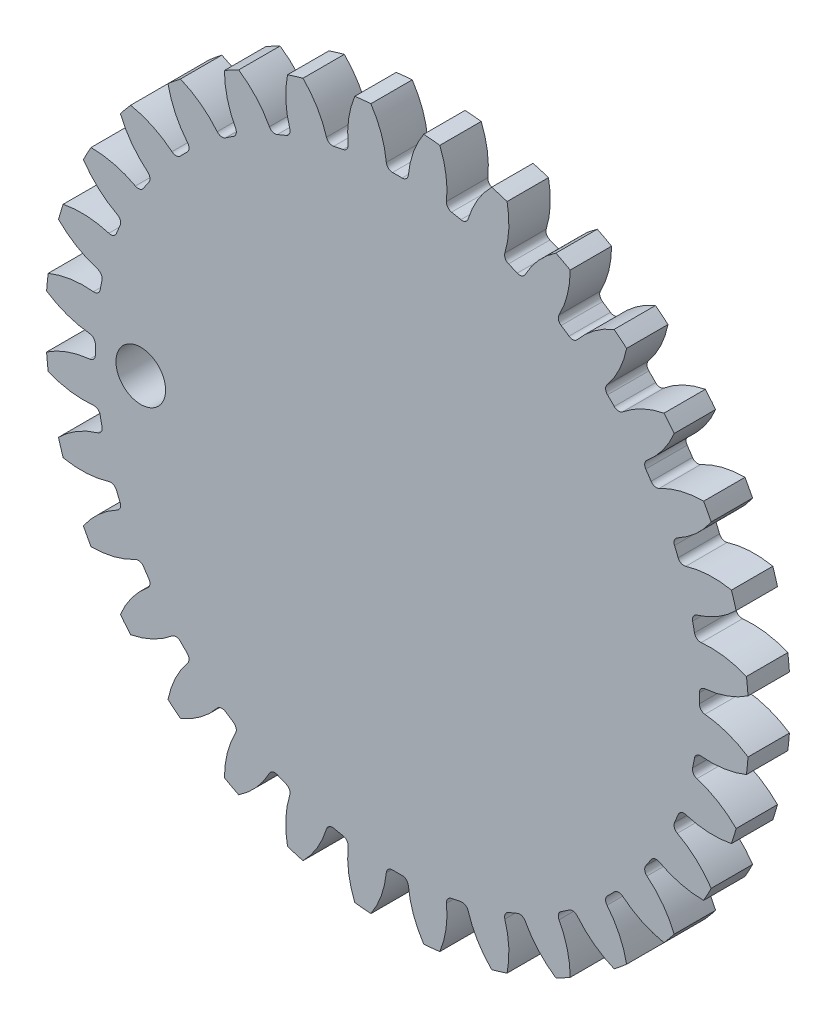
SolidWorks part; units mm, degrees
ref_plane "Front Plane" through (0, 0, 0) normal (0, 0, 1) x (1, 0, 0)
ref_plane "Top Plane" through (0, 0, 0) normal (0, 1, 0) x (1, 0, 0)
ref_plane "Right Plane" through (0, 0, 0) normal (1, 0, 0) x (0, 0, -1)
sketch "Sketch1" plane through (0, 0, 0) normal (0, 0, 1) x (1, 0, 0)
  circle A0 centre (0, 0) radius 50.8
  circle A1 centre (0, 0) radius 53.975
  circle A2 centre (0, 0) radius 46.355
  dimension "RootDiaCalc" = 101.6
  dimension "OutsideDiaCalc" = 107.95
  dimension "WholeDepthCalc" = 7.62
extrude "Boss-Extrude1" add sketch "Sketch1" along normal blind 6.35 contours A1
sketch "Sketch2" plane through (0, 0, 6.35) normal (0, 0, 1) x (1, 0, 0)
  line L0 (0, 0) -> (0, 53.975) construction
  line L1 (-2.4926, 50.7388) -> (2.4926, 50.7388) construction
  line L2 (-1.6341, 46.3262) -> (0, 0) construction
  line L3 (0, 43.8903) -> (-3.9819, 54.8306) construction
  line L4 (0, 0) -> (5.2905, 53.7151) construction
  line L5 (2.4926, 50.7388) -> (7.4539, 50.2502) construction
  circle A0 centre (0, 0) radius 53.975 construction
  arc A1 (-1.6341, 46.3262) -> (-4.749, 54.7695) centre (-16.0094, 45.8191) ccw
  arc A2 (1.6341, 46.3262) -> (4.749, 54.7695) centre (16.0094, 45.8191) cw
  circle A4 centre (0, 0) radius 46.355 construction
  arc A6 (1.6341, 46.3262) -> (-1.6341, 46.3262) centre (0, 0) ccw
  arc A7 (4.749, 54.7695) -> (-4.749, 54.7695) centre (0, 0) ccw
  circle A8 centre (0, 0) radius 53.975 construction
  circle A9 centre (0, 0) radius 50.8 construction
  dimension "SafetyOffset" = 1
  dimension "PressureAngleCalc" = 20
  dimension "AngleLineUpCalc" = 5.625
extrude "Cut-Extrude1" cut sketch "Sketch2" against normal up to surface (6.35 mm away) up to face at (53.975, 0, 0)
fillet "Fillet1" radius 0.9525 2 edges at (1.6341, 46.3262, 3.175) (-1.6341, 46.3262, 3.175)
pattern_circular "CirPattern1" count 32 over 360 about axis through (0, 0, 0) along (0, 0, 1) of "Cut-Extrude1", "Fillet1"
sketch "Sketch4" plane through (0, 0, 0) normal (0, 0, -1) x (-1, 0, 0)
  circle A0 centre (0, 0) radius 12.065
  dimension "D1" = 24.13
extrude "Boss-Extrude2" add sketch "Sketch4" along normal blind 6.35
sketch "Sketch7" plane through (0, 0, 0) normal (0, 0, -1) x (-1, 0, 0)
  line L1 (39.37, 0) -> (0, 0) construction
  circle A0 centre (39.37, 0) radius 3.81
  dimension "D1" = 7.62
  dimension "D2" = 39.37
extrude "Cut-Extrude2" cut sketch "Sketch7" against normal through all
equation "\"Module\"= \"Root Diameter\" / \"Number of Teeth\""
equation "\"Number of Teeth\"= 32"
equation "\"RootDiaCalc@Sketch1\" = \"Module\" * \"Number of Teeth\""
equation "\"OutsideDiaCalc@Sketch1\" = \"Module\" *  ( \"Number of Teeth\" + 2 ) "
equation "\"WholeDepthCalc@Sketch1\" = \"Module\" * IIF ( \"Module\" =  > 1.25 , 2.25 , 2.4 ) "
equation "\"AngleLineUpCalc@Sketch2\" = 180 / \"Number of Teeth\""
equation "\"D1@Fillet1\"=\"Module\"*0.3"
equation "\"D1@CirPattern1\"=\"Number of Teeth\""
equation "\"Pressure Angle\"= 20deg"
equation "\"PressureAngleCalc@Sketch2\"=\"Pressure Angle\""
equation "\"Root Diameter\"= 4"
equation "\"Gear Width\"= 0.25"
equation "\"D1@Boss-Extrude1\"=\"Gear Width\""
equation "\"Circular Pitch\"= \"Root Diameter\" * 3.141592 / \"Number of Teeth\""
